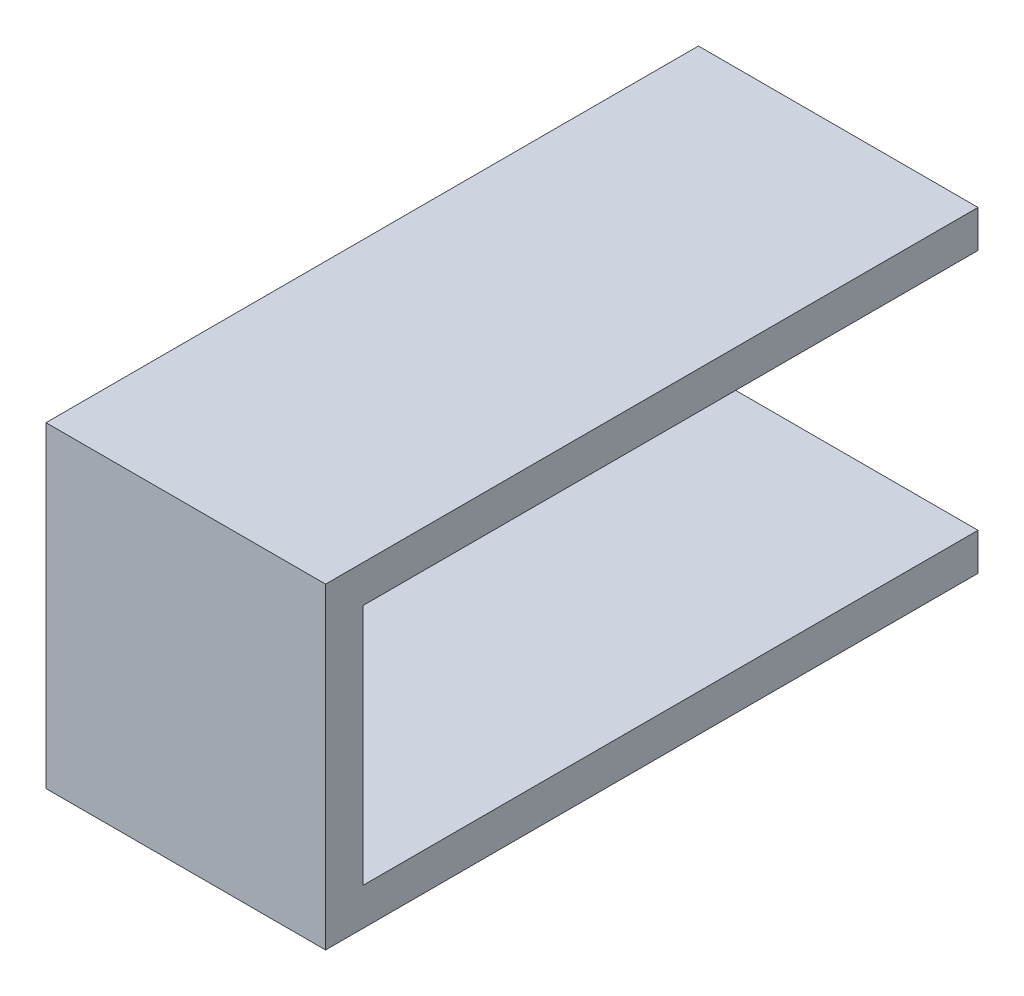
SolidWorks part; units mm, degrees
ref_plane "Front Plane" through (0, 0, 0) normal (1, 0, 0) x (0, 1, 0)
ref_plane "Top Plane" through (0, 0, 0) normal (0, 0, 1) x (0, 1, 0)
ref_plane "Right Plane" through (0, 0, 0) normal (0, 1, 0) x (-1, 0, 0)
sketch "Sketch1" plane through (0, 0, 0) normal (1, 0, 0) x (0, 1, 0)
  line L0 (-16.51, -41.91) -> (-16.51, 41.91)
  line L1 (-16.51, -41.91) -> (16.51, -41.91) construction
  line L2 (-16.51, -41.91) -> (-16.51, 41.91) construction
  line L3 (-16.51, 41.91) -> (16.51, 41.91) construction
  line L4 (16.51, -41.91) -> (16.51, 41.91) construction
  line L5 (-16.51, -41.91) -> (16.51, 41.91) construction
  line L6 (-16.51, 41.91) -> (16.51, -41.91) construction
  line L7 (-16.51, 41.91) -> (16.51, 41.91)
  line L8 (16.51, 41.91) -> (16.51, -41.91)
  line L9 (16.51, -41.91) -> (21.59, -41.91)
  line L10 (21.59, -41.91) -> (21.59, 46.99)
  line L11 (21.59, 46.99) -> (-21.59, 46.99)
  line L12 (-21.59, 46.99) -> (-21.59, -41.91)
  line L13 (-21.59, -41.91) -> (-16.51, -41.91)
  point P0 (0, 0)
  dimension "D1" = 33.02
  dimension "D2" = 83.82
  dimension "D3" = 5.08
  dimension "D4" = 5.08
  dimension "D5" = 5.08
extrude "Boss-Extrude1" add sketch "Sketch1" along normal blind 38.1
